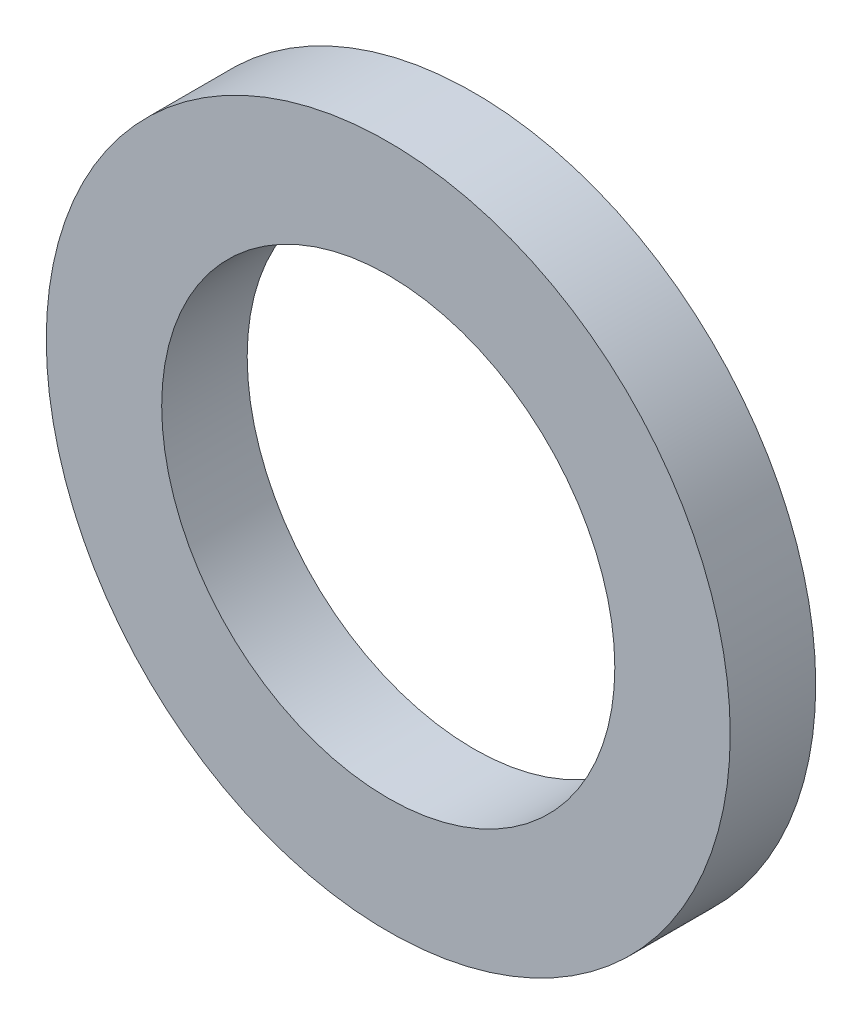
SolidWorks part; units mm, degrees
ref_plane "Alzado" through (0, 0, 0) normal (0, 0, 1) x (1, 0, 0)
ref_plane "Planta" through (0, 0, 0) normal (0, 1, 0) x (1, 0, 0)
ref_plane "Vista lateral" through (0, 0, 0) normal (1, 0, 0) x (0, 0, -1)
sketch "Croquis1" plane through (0, 0, 0) normal (0, 0, 1) x (1, 0, 0)
  circle A0 centre (0, 0) radius 2.65
  circle A1 centre (0, 0) radius 4
  dimension "D1" = 5.3
  dimension "D2" = 8
extrude "Saliente-Extruir1" add sketch "Croquis1" along normal blind 1 contours A0 | A1
